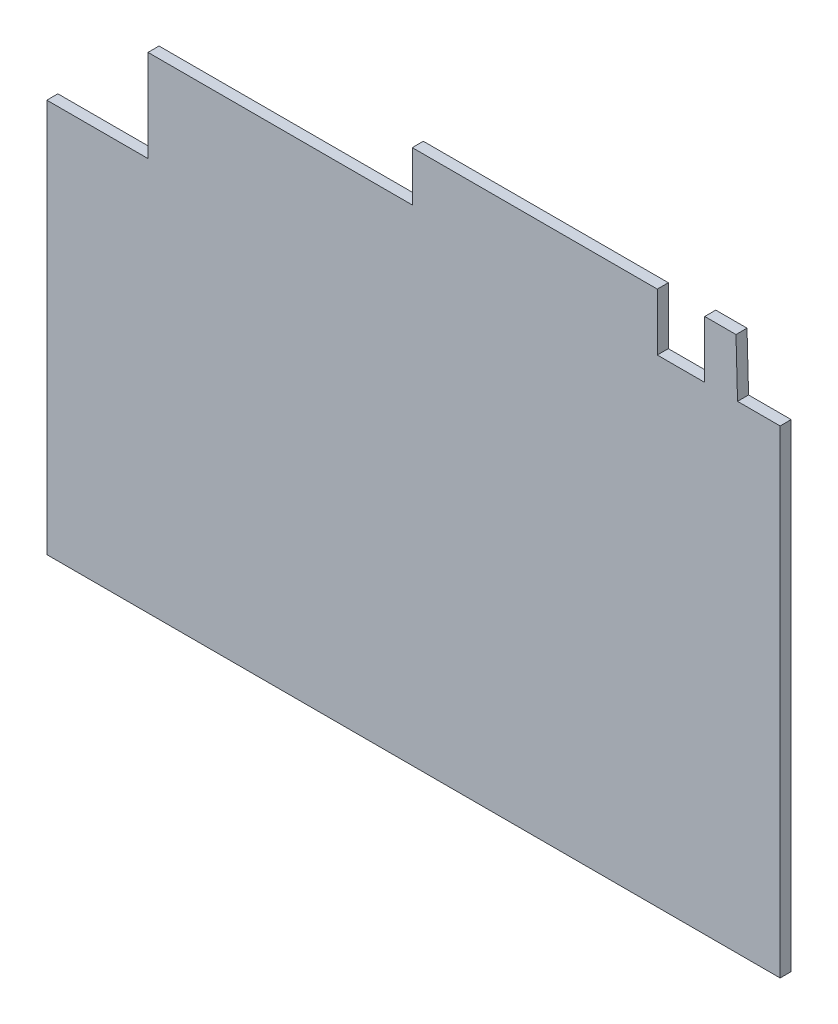
SolidWorks part; units mm, degrees
material "ABS"
ref_plane "Front Plane" through (0, 0, 0) normal (0, 0, 1) x (1, 0, 0)
ref_plane "Top Plane" through (0, 0, 0) normal (0, 1, 0) x (1, 0, 0)
ref_plane "Right Plane" through (0, 0, 0) normal (1, 0, 0) x (0, 0, -1)
sketch "Sketch1" plane through (0, 0, 0) normal (0, 0, 1) x (1, 0, 0)
  line L0 (28.5714, 236.0602) -> (28.5714, 237.0518)
  line L1 (28.5714, 277.1048) -> (28.5714, -22.8952) construction
  line L2 (28.5714, 237.0518) -> (5.4155, 237.0518)
  line L3 (5.4155, 237.0518) -> (4.5714, 268.1048)
  line L4 (4.5714, 268.1048) -> (-12.4286, 268.1048)
  line L5 (-12.4286, 268.1048) -> (-12.4286, 237.0518)
  line L6 (-12.4286, 237.0518) -> (-38.2166, 237.0518)
  line L7 (-38.2166, 237.0518) -> (-38.2166, 268.1048)
  line L8 (-221.4286, 268.1048) -> (28.5714, 268.1048) construction
  line L9 (-38.2166, 268.1048) -> (-171.4286, 268.1048)
  line L10 (-171.4286, 268.1048) -> (-171.4286, 241.1048)
  line L11 (-171.4286, 241.1048) -> (-370.1235, 241.1048)
  line L12 (-370.1235, 241.1048) -> (-370.1235, -22.8952)
  line L13 (-370.1235, -22.8952) -> (28.5714, -22.8952)
  line L14 (28.5714, -22.8952) -> (28.5714, 236.0602)
extrude "Boss-Extrude1" add sketch "Sketch1" along normal blind 6
sketch "Sketch2" plane through (0, 0, 6) normal (0, 0, 1) x (1, 0, 0)
  line L1 (-370.1235, 241.1048) -> (-315.1235, 241.1048)
  line L2 (-370.1235, 241.1048) -> (-370.1235, 191.1048)
  line L3 (-370.1235, 191.1048) -> (-315.1235, 191.1048)
  line L4 (-315.1235, 241.1048) -> (-315.1235, 191.1048)
  dimension "D1" = 55
  dimension "D2" = 50
extrude "Cut-Extrude1" cut sketch "Sketch2" against normal blind 10
